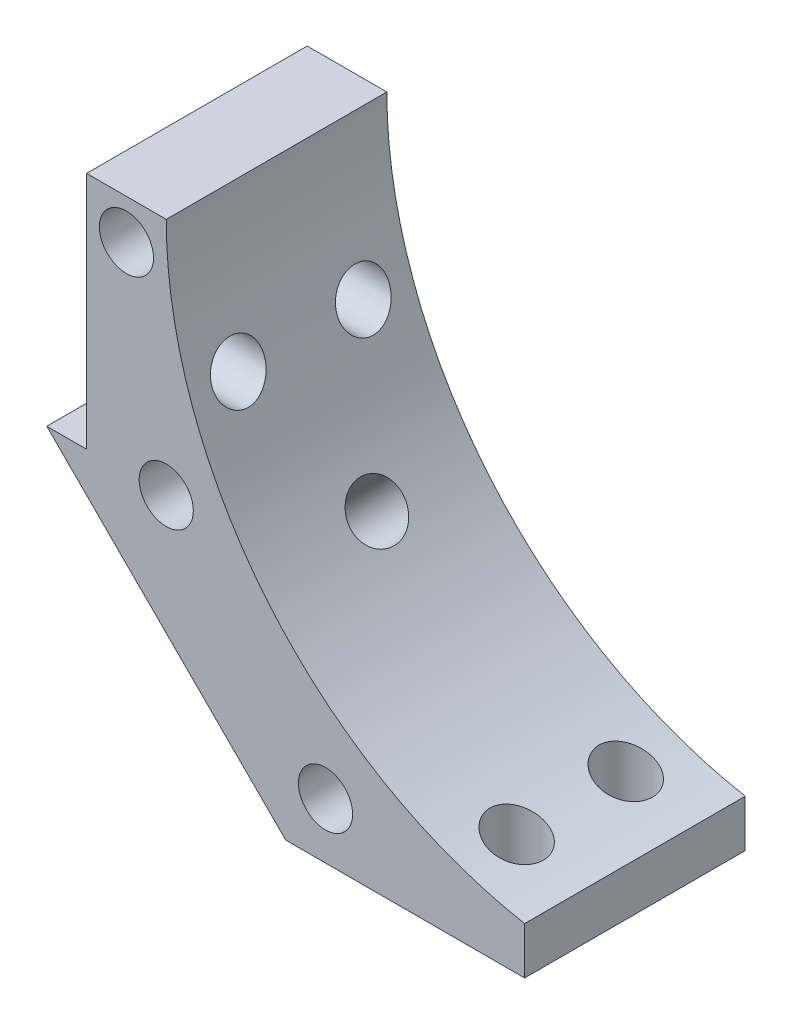
SolidWorks part; units mm, degrees
ref_plane "前视基准面" through (0, 0, 0) normal (0, 0, 1) x (1, 0, 0)
ref_plane "上视基准面" through (0, 0, 0) normal (0, 1, 0) x (1, 0, 0)
ref_plane "右视基准面" through (0, 0, 0) normal (1, 0, 0) x (0, 0, -1)
other "Configuration Table"
sketch "草图1" plane through (0, 0, 0) normal (0, 0, 1) x (1, 0, 0)
  line L0 (0, 30) -> (30, 0)
  line L1 (0, 0) -> (30, 0)
  line L2 (0, 0) -> (0, 30)
  line L3 (0, 30) -> (30, 30)
  line L4 (30, 0) -> (30, 30)
  line L6 (30, 30) -> (60, 30)
  line L7 (30, 30) -> (30, 0)
  line L8 (30, 0) -> (60, 0)
  line L9 (60, 30) -> (60, 0)
  line L10 (5, 30) -> (30, 30)
  line L11 (5, 30) -> (5, 60)
  line L12 (5, 60) -> (30, 60)
  line L13 (30, 30) -> (30, 60)
  dimension "D1" = 30
  dimension "D2" = 30
  dimension "D3" = 30
  dimension "D4" = 30
  dimension "D5" = 5
extrude "凸台-拉伸1" add sketch "草图1" along normal blind 27.7 contours L0 L4 L3 | L7 L6 L9 L8 | L11 L10 L13 L12
sketch "草图3" plane through (0, 0, 27.7) normal (0, 0, 1) x (1, 0, 0)
  line L0 (30, 0) -> (60, 0) construction
  line L1 (0, 30) -> (0, 105.7176) construction
  line L6 (0, 30) -> (30, 0)
  line L7 (30, 0) -> (60, 0)
  line L8 (60, 0) -> (60, 30)
  line L9 (5, 30) -> (0, 30)
  line L10 (0, 30) -> (30, 0)
  line L11 (30, 0) -> (60, 0)
  line L12 (60, 0) -> (60, 30)
  line L13 (5, 30) -> (0, 30)
  line L18 (60, 30) -> (30, 30)
  line L19 (60, 30) -> (30, 30)
  line L20 (30, 30) -> (30, 60)
  line L21 (30, 30) -> (30, 60)
  line L22 (30, 60) -> (5, 60)
  line L23 (30, 60) -> (5, 60)
  line L24 (5, 60) -> (5, 30)
  line L25 (5, 60) -> (5, 30)
  circle A0 centre (70, 60) radius 55
  line M4 (5, 30) -> (0, 30)
  dimension "D1" = 110
  dimension "D2" = 60
  dimension "D3" = 70
  dimension "D4" = 0
extrude "切除-拉伸1" cut sketch "草图3" against normal blind 40 contours A0 L12 M4
sketch "草图4" plane through (0, 0, 27.7) normal (0, 0, 1) x (1, 0, 0)
  line L6 (15, 60) -> (5, 60)
  line L7 (5, 60) -> (5, 30)
  line L8 (5, 30) -> (0, 30)
  line L9 (0, 30) -> (30, 0)
  line L10 (30, 0) -> (60, 0)
  line L11 (60, 0) -> (60, 5.9167)
  line L12 (15, 60) -> (5, 60)
  line L13 (5, 60) -> (5, 30)
  line L14 (5, 30) -> (0, 30)
  line L15 (0, 30) -> (30, 0)
  line L16 (30, 0) -> (60, 0)
  line L17 (60, 0) -> (60, 5.9167)
  arc A1 (15, 60) -> (60, 5.9167) centre (70, 60) ccw
  arc A2 (15, 60) -> (60, 5.9167) centre (70, 60) ccw
  circle A3 centre (35, 7) radius 3.4
  circle A4 centre (10, 55) radius 3.4
  circle A5 centre (15, 30) radius 3.4
  dimension "D2" = 6.8
  dimension "D3" = 30
  dimension "D4" = 6.8
  dimension "D5" = 6.8
  dimension "D9" = 25
  dimension "D10" = 7
  dimension "D6" = 5
  dimension "D7" = 5
  dimension "D8" = 10
  dimension "D1" = 0
extrude "切除-拉伸2" cut sketch "草图4" against normal through all contours A4 | A5 | A3
sketch "草图5" plane through (5, 0, 0) normal (-1, 0, 0) x (0, 0, 1)
  line L0 (27.7, 30) -> (0, 30) construction
  line L1 (27.7, 30) -> (27.7, 60) construction
  line L2 (0, 30) -> (0, 60) construction
  circle A0 centre (6, 42) radius 3.3
  circle A1 centre (21.7, 42) radius 3.3
  dimension "D1" = 6.6
  dimension "D2" = 6.6
  dimension "D3" = 12
  dimension "D4" = 12
  dimension "D5" = 6
  dimension "D6" = 6
extrude "切除-拉伸3" cut sketch "草图5" against normal through all
sketch "草图6" plane through (0, 0, 0) normal (0, -1, 0) x (1, 0, 0)
  line L0 (60, 27.7) -> (60, 0) construction
  line L1 (30, 27.7) -> (60, 27.7) construction
  line L2 (30, 0) -> (60, 0) construction
  circle A0 centre (52, 20.7) radius 3.35
  circle A1 centre (52, 7) radius 3.35
  dimension "D3" = 6.7
  dimension "D4" = 6.7
  dimension "D1" = 8
  dimension "D2" = 8
  dimension "D5" = 7
  dimension "D6" = 7
extrude "切除-拉伸4" cut sketch "草图6" against normal through all
sketch "草图7" plane through (0, 0, 0) normal (0, 0, -1) x (-1, 0, 0)
  line L6 (-5, 60) -> (-15, 60)
  line L7 (-60, 5.9167) -> (-60, 0)
  line L8 (-60, 0) -> (-30, 0)
  line L9 (-30, 0) -> (0, 30)
  line L10 (0, 30) -> (-5, 30)
  line L11 (-5, 30) -> (-5, 60)
  line L12 (-5, 60) -> (-15, 60)
  line L13 (-60, 5.9167) -> (-60, 0)
  line L14 (-60, 0) -> (-30, 0)
  line L15 (-30, 0) -> (0, 30)
  line L16 (0, 30) -> (-5, 30)
  line L17 (-5, 30) -> (-5, 60)
  arc A1 (-60, 5.9167) -> (-15, 60) centre (-70, 60) ccw
  arc A2 (-60, 5.9167) -> (-15, 60) centre (-70, 60) ccw
  dimension "D1" = 0
extrude "凸台-拉伸2" add sketch "草图7" along normal blind 50
sketch "草图8" plane through (15, 15, 0) normal (-0.7071, -0.7071, 0) x (0, 0, 1)
  line L0 (-50, 0) -> (27.7, 0)
  line L1 (-50, -21.2132) -> (-50, 21.2132) construction
  line L2 (27.7, 21.2132) -> (27.7, -21.2132) construction
  circle A0 centre (12.7, 0) radius 3.4
  circle A1 centre (-40, 10) radius 3.4
  circle A2 centre (-40, -10) radius 3.4
  circle A3 centre (-20, -10) radius 3.4
  circle A4 centre (-20, 10) radius 3.4
  dimension "D1" = 6.8
  dimension "D2" = 15
  dimension "D3" = 6.8
  dimension "D4" = 10
  dimension "D5" = 10
  dimension "D9" = 20
  dimension "D7" = 10
  dimension "D6" = 2
  dimension "D8" = 2
extrude "切除-拉伸5" cut sketch "草图8" against normal blind 50 contours L0 A0 | L0 A0 | A1 | A4 | A2 | A3
sketch "草图9" plane through (0, 0, -50) normal (0, 0, -1) x (-1, 0, 0)
  line L6 (-5, 30) -> (-5, 60)
  line L7 (-5, 60) -> (-15, 60)
  line L8 (-60, 5.9167) -> (-60, 0)
  line L9 (-60, 0) -> (-30, 0)
  line L10 (-30, 0) -> (0, 30)
  line L11 (0, 30) -> (-5, 30)
  line L12 (-5, 30) -> (-5, 60)
  line L13 (-5, 60) -> (-15, 60)
  line L14 (-60, 5.9167) -> (-60, 0)
  line L15 (-60, 0) -> (-30, 0)
  line L16 (-30, 0) -> (0, 30)
  line L17 (0, 30) -> (-5, 30)
  arc A1 (-60, 5.9167) -> (-15, 60) centre (-70, 60) ccw
  arc A2 (-60, 5.9167) -> (-15, 60) centre (-70, 60) ccw
  dimension "D1" = 0
extrude "切除-拉伸6" cut sketch "草图9" against normal blind 50
